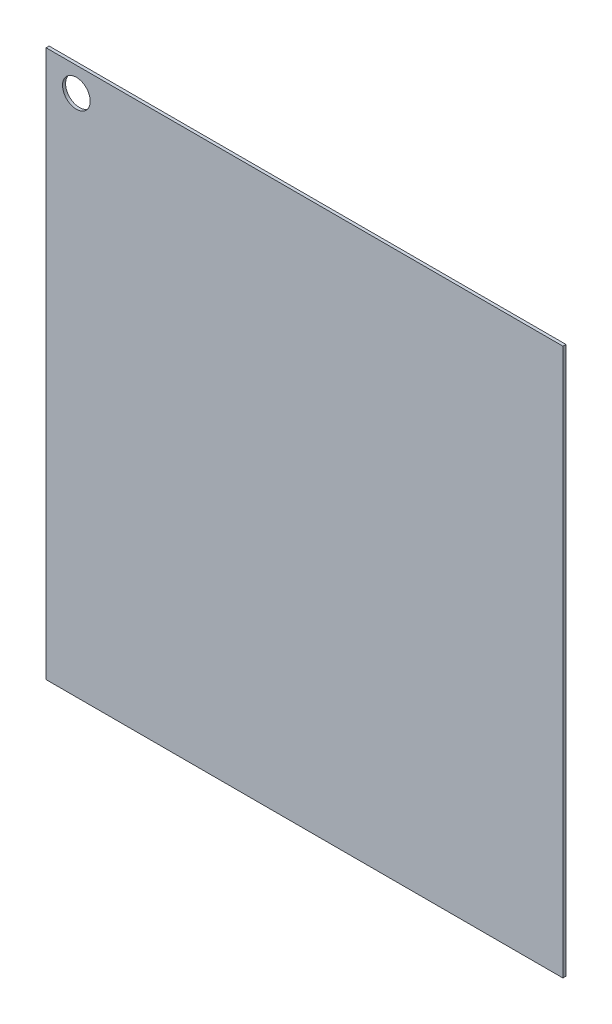
SolidWorks part; units mm, degrees
ref_plane "Front Plane" through (0, 0, 0) normal (0, 0, 1) x (1, 0, 0)
ref_plane "Top Plane" through (0, 0, 0) normal (0, 1, 0) x (1, 0, 0)
ref_plane "Right Plane" through (0, 0, 0) normal (1, 0, 0) x (0, 0, -1)
sketch "Sketch1" plane through (0, 0, 0) normal (0, 0, 1) x (1, 0, 0)
  line L1 (255, -270) -> (-255, -270)
  line L2 (255, -270) -> (255, 270)
  line L3 (255, 270) -> (-255, 270)
  line L4 (-255, -270) -> (-255, 270)
  line L5 (255, -270) -> (-255, 270) construction
  line L6 (255, 270) -> (-255, -270) construction
  point P0 (0, 0)
  dimension "D1" = 510
  dimension "D2" = 540
extrude "Boss-Extrude1" add sketch "Sketch1" along normal blind 3
sketch "Sketch2" plane through (0, 0, 3) normal (0, 0, 1) x (1, 0, 0)
  circle A0 centre (-225.0929, 246.0426) radius 13.6583
extrude "Cut-Extrude1" cut sketch "Sketch2" against normal up to next
